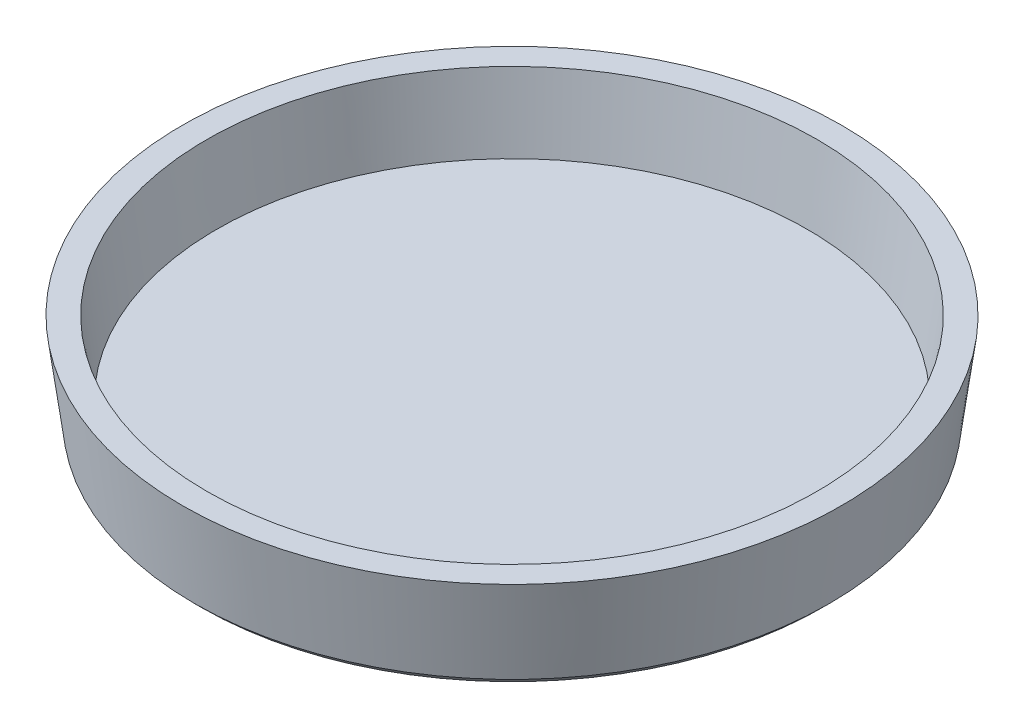
SolidWorks part; units mm, degrees
material "PLA"
ref_plane "Front Plane" through (0, 0, 0) normal (0, 0, 1) x (1, 0, 0)
ref_plane "Top Plane" through (0, 0, 0) normal (0, 1, 0) x (1, 0, 0)
ref_plane "Right Plane" through (0, 0, 0) normal (1, 0, 0) x (0, 0, -1)
sketch "Sketch1" plane through (0, 0, 0) normal (1, 0, 0) x (0, 0, -1)
  line L0 (0, 0) -> (0, -14.8254) construction
  line L1 (0, 0) -> (41.275, 0)
  line L2 (41.275, 0) -> (42.9515, 12.7)
  line L3 (42.9515, 12.7) -> (0, 12.7)
  line L4 (0, 12.7) -> (0, 0)
  dimension "D1" = 82.55
  dimension "D2" = 97.52
  dimension "D3" = 12.7
revolve "Revolve1" add sketch "Sketch1" angle 360 about L0
shell "Shell1" thickness 3.175
chamfer "Chamfer1" distance 0.762 angle 45 1 edges at (0, 0, 41.275)
